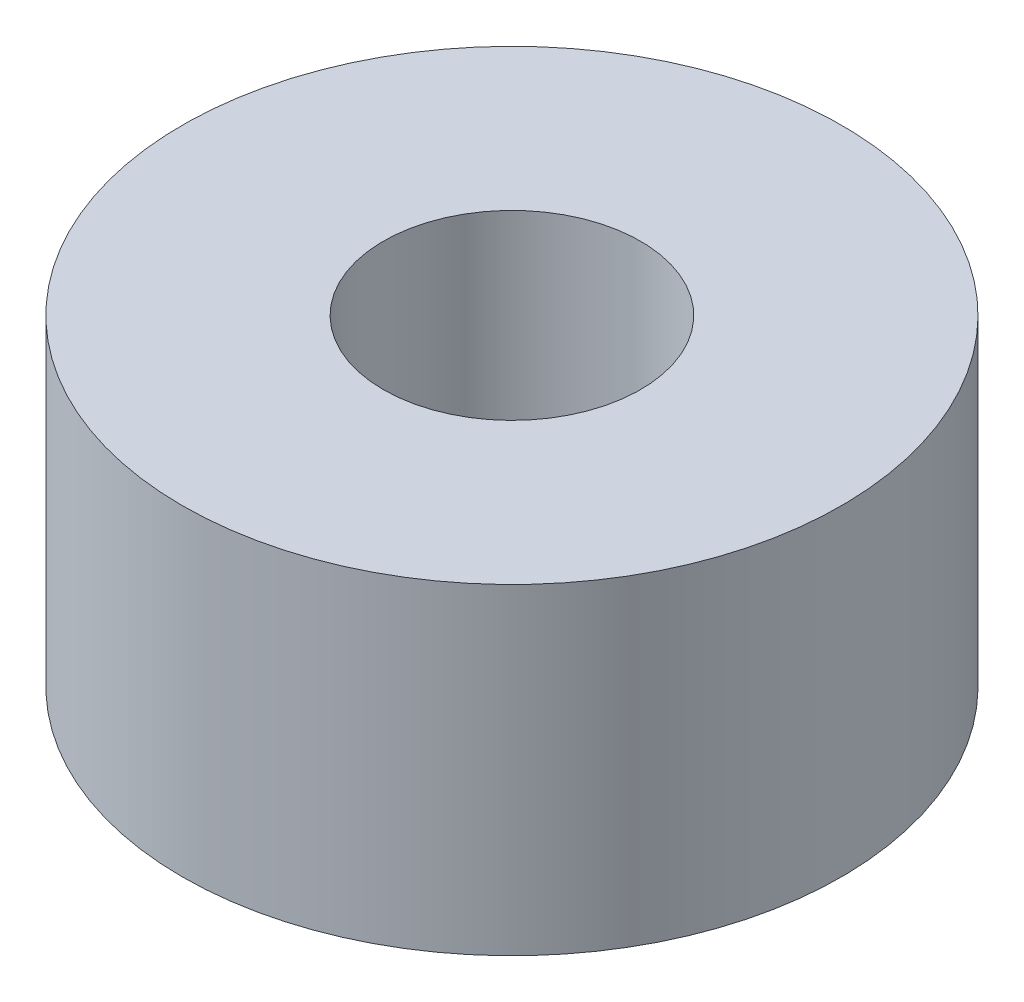
SolidWorks part; units mm, degrees
ref_plane "Front Plane" through (0, 0, 0) normal (0, 0, 1) x (1, 0, 0)
ref_plane "Top Plane" through (0, 0, 0) normal (0, 1, 0) x (1, 0, 0)
ref_plane "Right Plane" through (0, 0, 0) normal (1, 0, 0) x (0, 0, -1)
sketch "Sketch1" plane through (0, 0, 0) normal (0, 1, 0) x (1, 0, 0)
  circle A0 centre (0, 0) radius 2.032
  circle A1 centre (0, 0) radius 5.207
  dimension "D1" = 4.064
  dimension "D2" = 3.175
extrude "Boss-Extrude1" add sketch "Sketch1" along normal blind 5.08
